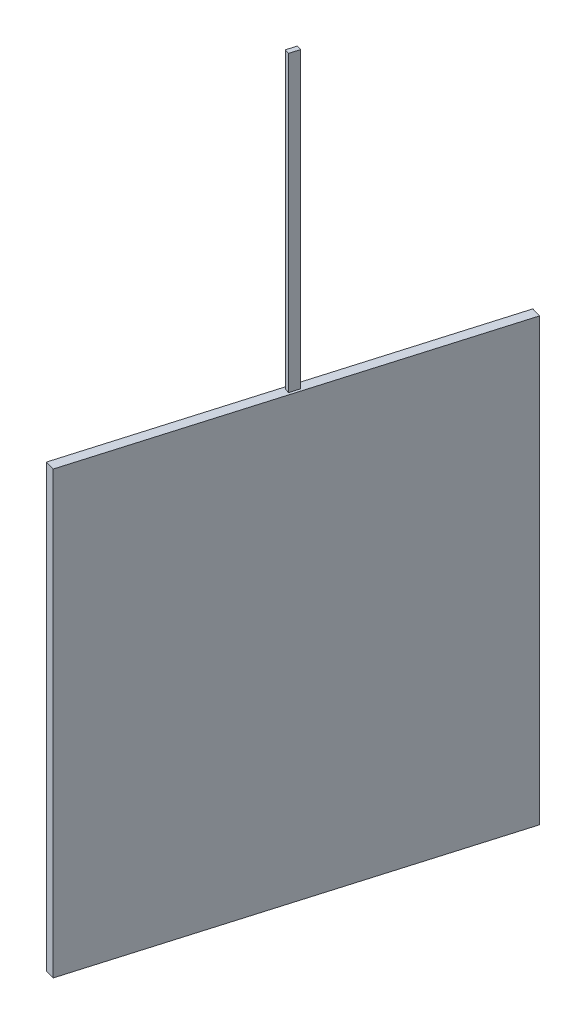
SolidWorks part; units mm, degrees
ref_plane "Front Plane" through (0, 0, 0) normal (0, 0, 1) x (1, 0, 0)
ref_plane "Top Plane" through (0, 0, 0) normal (0, 1, 0) x (1, 0, 0)
ref_plane "Right Plane" through (0, 0, 0) normal (1, 0, 0) x (0, 0, -1)
sketch "Sketch1" plane through (0, 0, 0) normal (0, 1, 0) x (1, 0, 0)
  line L4 (-1.2184, 0.3584) -> (1.2184, -0.3584)
  line L5 (1.2184, -0.3584) -> (-27.4497, -97.8299)
  line L6 (-27.4497, -97.8299) -> (-29.8865, -97.1132)
  line L7 (-29.8865, -97.1132) -> (-1.2184, 0.3584)
  line L8 (0, -55) -> (0, 55) construction
  point P0 (0, 0)
  dimension "D1" = 2.54
  dimension "D2" = 101.6
  dimension "D3" = 16.39
extrude "Boss-Extrude1" add sketch "Sketch1" against normal blind 114.3
sketch "Sketch2" plane through (0, 0, 0) normal (0, 1, 0) x (1, 0, 0)
  line L0 (-14.5849, -47.3382) -> (-15.3016, -49.775)
  line L1 (-15.3016, -49.775) -> (-14.0832, -50.1333)
  line L2 (-14.0832, -50.1333) -> (-13.3665, -47.6965)
  line L3 (-13.3665, -47.6965) -> (-14.5849, -47.3382)
  line L5 (-27.4497, -97.8299) -> (1.2184, -0.3584) construction
  line L7 (1.2184, -0.3584) -> (-1.2184, 0.3584) construction
  point P5 (-13.9757, -47.5174)
  point P9 (-13.7249, -48.9149)
  dimension "D1" = 2.54
  dimension "D2" = 1.27
  dimension "D3" = 1.27
  dimension "D4" = 50.8
extrude "Boss-Extrude2" add sketch "Sketch2" along normal blind 76.2
